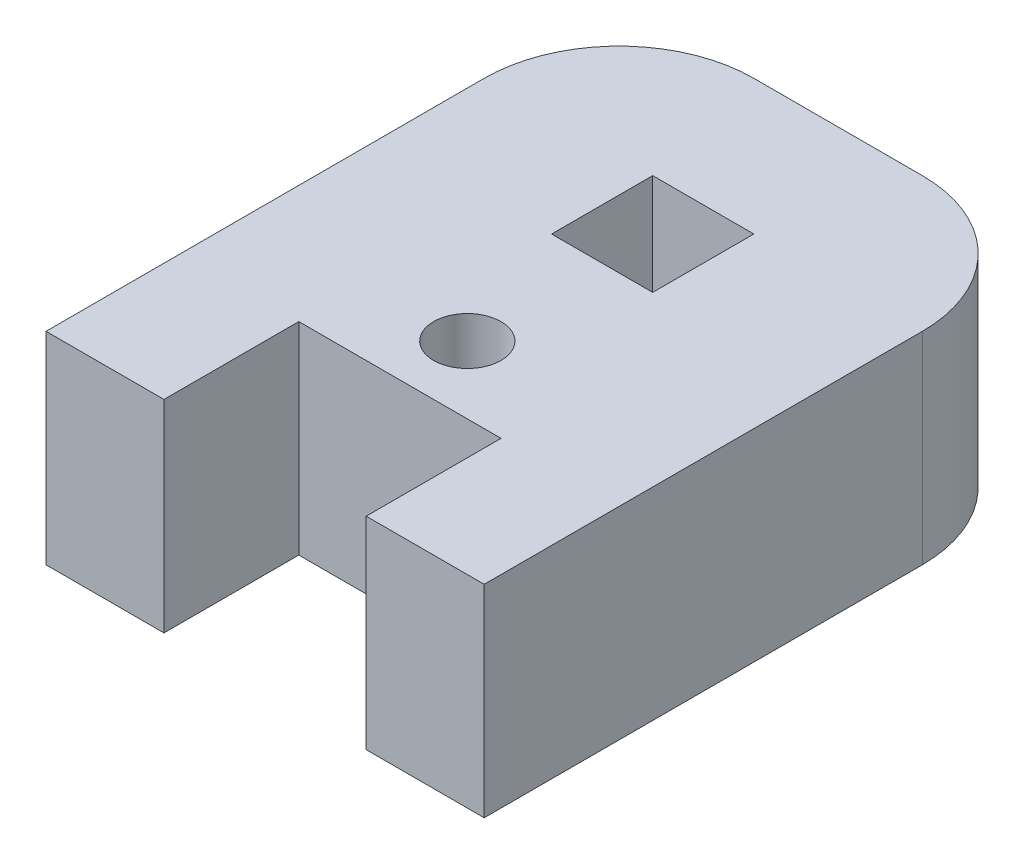
SolidWorks part; units mm, degrees
ref_plane "Front Plane" through (0, 0, 0) normal (0, 0, 1) x (1, 0, 0)
ref_plane "Top Plane" through (0, 0, 0) normal (0, 1, 0) x (1, 0, 0)
ref_plane "Right Plane" through (0, 0, 0) normal (1, 0, 0) x (0, 0, -1)
sketch "Sketch1" plane through (0, 0, 0) normal (0, 1, 0) x (1, 0, 0)
  line L0 (3.5, 0) -> (3.5, 4)
  line L1 (0, 0) -> (3.5, 0)
  line L2 (0, 0) -> (0, 17)
  line L3 (0, 17) -> (13, 17)
  line L4 (13, 0) -> (13, 17)
  line L5 (3.5, 4) -> (9.5, 4)
  line L6 (9.5, 4) -> (9.5, 0)
  line L7 (9.5, 0) -> (13, 0)
  dimension "D1" = 13
  dimension "D2" = 13
  dimension "D3" = 4
  dimension "D4" = 6
  dimension "D5" = 3.5
extrude "Boss-Extrude1" add sketch "Sketch1" along normal blind 6
sketch "Sketch2" plane through (0, 6, 0) normal (0, 1, 0) x (1, 0, 0)
  line L0 (3.5, 4) -> (9.5, 4) construction
  line L1 (5, 13) -> (8, 13)
  line L2 (5, 13) -> (5, 10)
  line L3 (5, 10) -> (8, 10)
  line L4 (8, 13) -> (8, 10)
  line L6 (13, 17) -> (0, 17) construction
  circle A0 centre (6.5, 6) radius 1
  point P8 (5, 11.5)
  point P11 (6.5, 10)
  point P12 (6.5, 4)
  point P13 (6.5, 13)
  dimension "D3" = 2
  dimension "D1" = 3
  dimension "D2" = 3
  dimension "D4" = 2
  dimension "D5" = 4
extrude "Cut-Extrude1" cut sketch "Sketch2" against normal through all
fillet "Fillet1" radius 4 2 edges at (13, 3, -17) (0, 3, -17)
